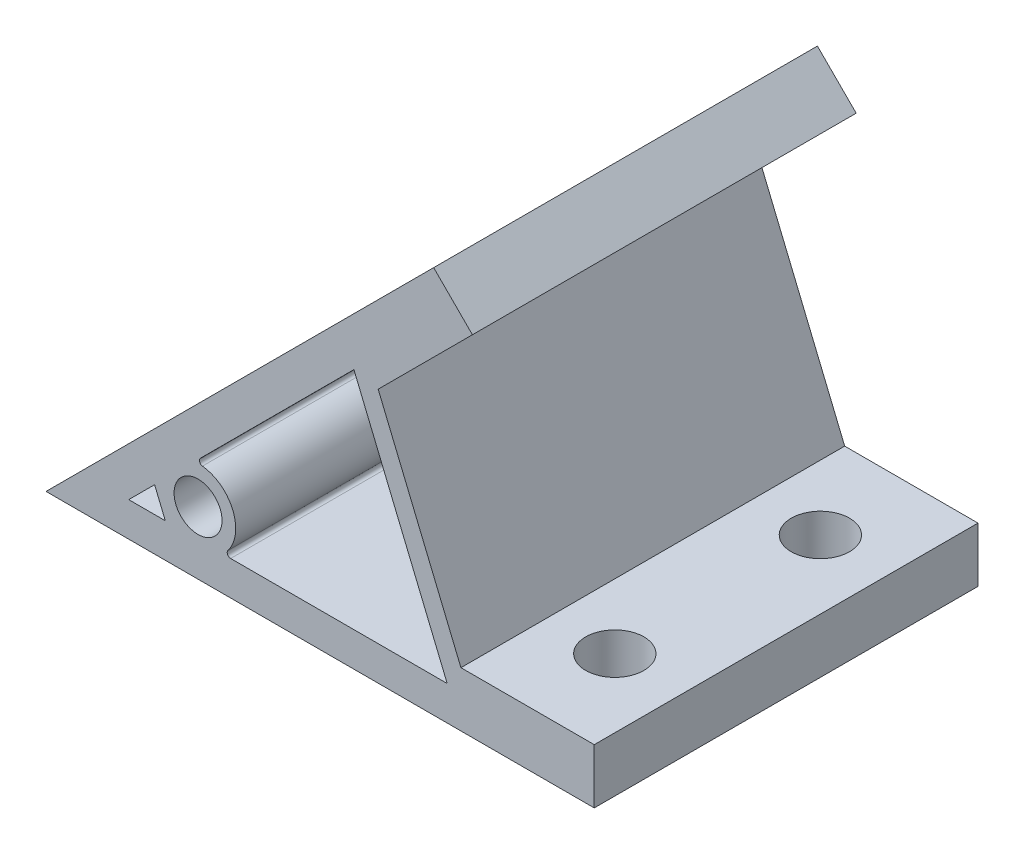
SolidWorks part; units mm, degrees
ref_plane "前视基准面" through (0, 0, 0) normal (0, 0, 1) x (1, 0, 0)
ref_plane "上视基准面" through (0, 0, 0) normal (0, 1, 0) x (1, 0, 0)
ref_plane "右视基准面" through (0, 0, 0) normal (1, 0, 0) x (0, 0, -1)
sketch "草图1" plane through (0, 0, 0) normal (0, 0, 1) x (1, 0, 0)
  line L0 (0, 0) -> (56.5685, 56.5685)
  line L1 (0, 0) -> (80, 0)
  line L2 (12.0711, 5) -> (15.8477, 8.7766)
  line L3 (12.0711, 5) -> (17.412, 5)
  line L4 (15.8477, 8.7766) -> (17.412, 5)
  line L5 (0, 0) -> (16.6385, 6.8674) construction
  line L6 (22.5392, 15.4681) -> (44.9316, 37.8605)
  line L7 (26.9418, 5) -> (58.5429, 5)
  line L8 (12.0711, 5) -> (60.1041, 53.033) construction
  line L9 (58.5429, 5) -> (44.9316, 37.8605)
  line L10 (12.0711, 5) -> (80, 5) construction
  line L11 (60.5474, 8) -> (48.4704, 37.1566)
  line L12 (61.3145, 6.1481) -> (47.7033, 39.0086) construction
  line L13 (62.2254, 50.9117) -> (56.5685, 56.5685)
  line L14 (80, 0) -> (80, 8)
  line L15 (60.5474, 8) -> (80, 8)
  line L16 (50.7665, 39.4527) -> (62.2254, 50.9117) construction
  line L17 (48.4704, 37.1566) -> (62.2254, 50.9117)
  line L18 (63.7946, 8) -> (50.7665, 39.4527) construction
  line L19 (63.7946, 8) -> (80, 8) construction
  line L20 (61.7901, 5) -> (80, 5) construction
  line L21 (47.2277, 40.1566) -> (60.1041, 53.033) construction
  line L23 (61.7901, 5) -> (47.2277, 40.1566) construction
  circle A0 centre (22.1847, 9.1565) radius 3.5
  arc A1 (26.5454, 5.8047) -> (22.8337, 14.618) centre (22.1847, 9.1565) ccw
  arc A2 (26.9418, 5) -> (26.5454, 5.8047) centre (26.9418, 5.5) cw
  circle A3 centre (22.1847, 9.1565) radius 5.5 construction
  arc A4 (22.5392, 15.4681) -> (22.8337, 14.618) centre (22.8927, 15.1145) ccw
  point P15 (27.6847, 9.1565)
  point P20 (25.7866, 5)
  point P23 (21.7067, 14.6357)
  dimension "D7" = 7
  dimension "D8" = 2
  dimension "D9" = 0.5
  dimension "D10" = 56
  dimension "D1" = 45
  dimension "D2" = 80
  dimension "D4" = 67.5
  dimension "D5" = 18
  dimension "D6" = 6
  dimension "D3" = 5
  dimension "D11" = 3
  dimension "D12" = 3
extrude "凸台-拉伸1" add sketch "草图1" along normal mid plane 56
sketch "草图3" plane through (0, 0, 0) normal (0, -1, 0) x (1, 0, 0)
  line L1 (80, 28) -> (80, -28) construction
  line L2 (80, 0) -> (95.7601, 0) construction
  circle A0 centre (70, 15) radius 4.25
  circle A1 centre (70, -15) radius 4.25
  dimension "D1" = 15
  dimension "D2" = 10
  dimension "D3" = 8.5
extrude "切除-拉伸2" cut sketch "草图3" against normal blind 20
sketch "草图4" plane through (54.5089, 22.5783, 0) normal (0.9239, 0.3827, 0) x (0, 0, -1)
  line L0 (-28, 0) -> (28, 0) construction
  line L1 (-28, -15.7795) -> (-28, 15.7795) construction
  line L2 (28, -15.7795) -> (28, 15.7795) construction
ref_plane "基准面1" through (0, 0, 0) normal (0.3827, -0.9239, 0) x (-0.9239, -0.3827, 0)
mirror "镜向1" about plane through (0, 0, 0) normal (0.3827, -0.9239, 0) of "切除-拉伸2"
